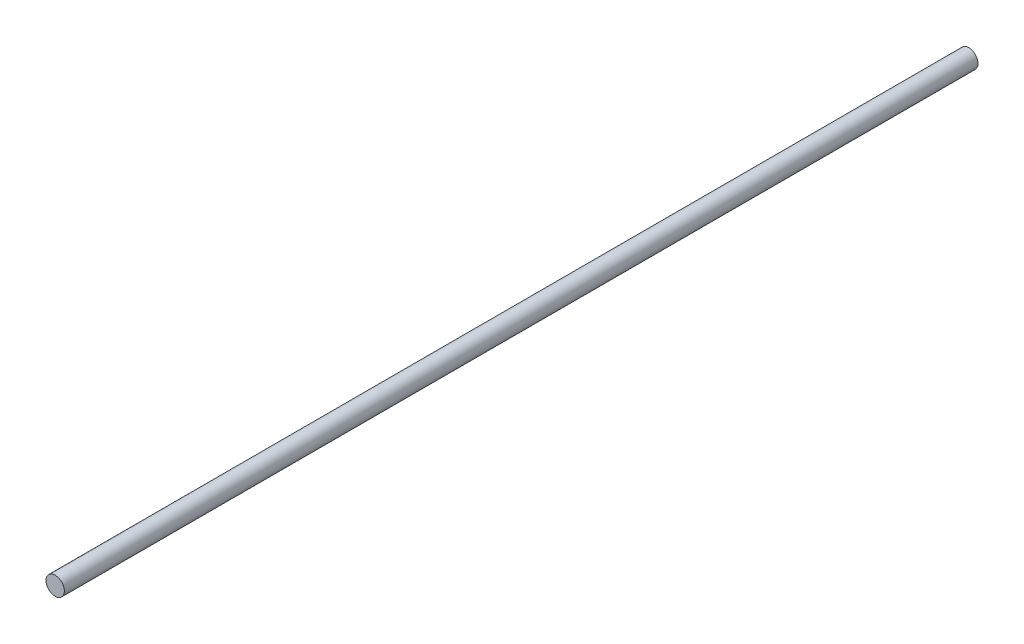
SolidWorks part; units mm, degrees
ref_plane "Ön Düzlem" through (0, 0, 0) normal (0, 0, 1) x (1, 0, 0)
ref_plane "Üst Düzlem" through (0, 0, 0) normal (0, 1, 0) x (1, 0, 0)
ref_plane "Sağ Düzlem" through (0, 0, 0) normal (1, 0, 0) x (0, 0, -1)
sketch "Çizim1" plane through (0, 0, 0) normal (0, 0, 1) x (1, 0, 0)
  circle A0 centre (0, 0) radius 6
  dimension "D1" = 12
extrude "Yükseklik-Ekstrüzyon1" add sketch "Çizim1" along normal blind 598
